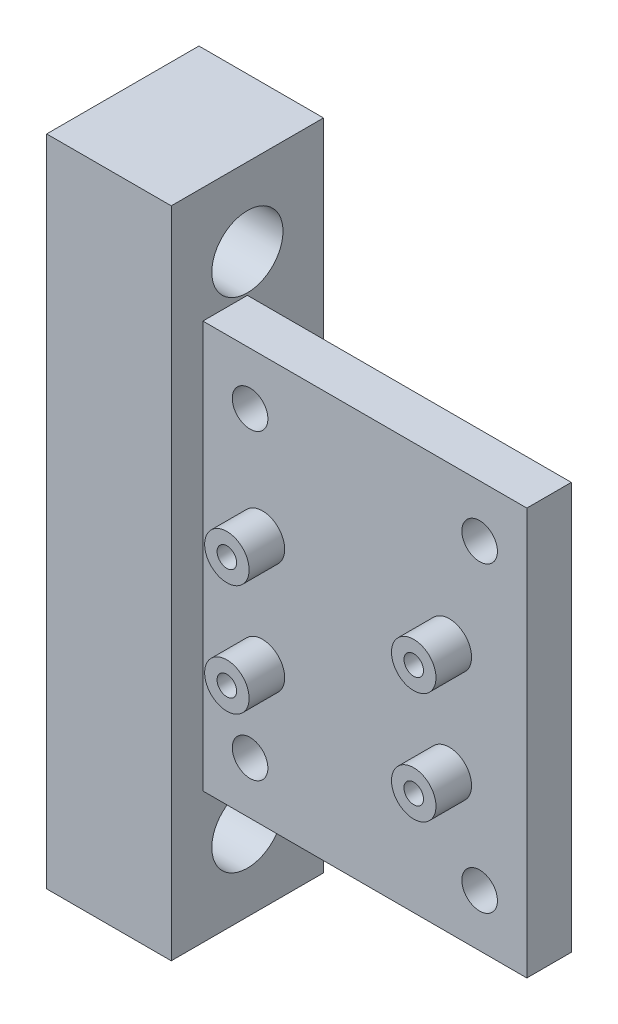
SolidWorks part; units mm, degrees
ref_plane "Ön Düzlem" through (0, 0, 0) normal (0, 0, 1) x (1, 0, 0)
ref_plane "Üst Düzlem" through (0, 0, 0) normal (0, 1, 0) x (1, 0, 0)
ref_plane "Sağ Düzlem" through (0, 0, 0) normal (1, 0, 0) x (0, 0, -1)
sketch "Çizim1" plane through (0, 0, 0) normal (0, 0, 1) x (1, 0, 0)
  line L5 (-17.8933, -21.9872) -> (18.5125, -21.9872)
  line L6 (24.7148, 0.8817) -> (-40.1845, 0.8817) construction
  line L7 (-17.8933, -21.9872) -> (-17.8933, 23.7507)
  line L8 (0.3096, 23.7507) -> (0.3096, -36.7823) construction
  line L9 (-17.8933, 23.7507) -> (18.5125, 23.7507)
  line L10 (18.5125, -21.9872) -> (18.5125, 23.7507)
  circle A0 centre (9.8019, 6.124) radius 1.1
  circle A1 centre (9.8019, -6.376) radius 1.1
  circle A2 centre (-11.1981, -6.376) radius 1.1
  circle A3 centre (-11.1981, 6.124) radius 1.1
  circle A4 centre (-11.1981, 6.124) radius 2.5
  circle A5 centre (9.8019, 6.124) radius 2.5
  circle A6 centre (9.8019, -6.376) radius 2.5
  circle A7 centre (-11.1981, -6.376) radius 2.5
  circle A12 centre (-12.5904, 17.8817) radius 2
  circle A13 centre (13.2096, 17.8817) radius 2
  circle A14 centre (13.2096, -16.1183) radius 2
  circle A15 centre (-12.5904, -16.1183) radius 2
  point P14 (0.3096, 0.8817)
extrude "Yükseklik-Ekstrüzyon3" add sketch "Çizim1" along normal blind 5 contours A7 A2 | A4 A3 | A5 A0 | A6 A1 | L5 L10 L9 L7 A15 A14 A13 A12 A7 A6 A5 A4
sketch "Çizim2" plane through (0, 0, 5) normal (0, 0, 1) x (1, 0, 0)
  circle A0 centre (-11.1981, 6.124) radius 2.5
  circle A1 centre (-11.1981, -6.376) radius 2.5
  circle A2 centre (9.8019, -6.376) radius 2.5
  circle A3 centre (9.8019, 6.124) radius 2.5
  dimension "D1" = 5
extrude "Yükseklik-Ekstrüzyon4" add sketch "Çizim2" along normal blind 4
sketch "Çizim3" plane through (0, 0, 5) normal (0, 0, -1) x (-1, 0, 0)
  circle A0 centre (11.1981, 6.124) radius 1.1 construction
  circle A1 centre (11.1981, -6.376) radius 1.1 construction
  circle A2 centre (-9.8019, -6.376) radius 1.1 construction
  circle A3 centre (-9.8019, 6.124) radius 1.1 construction
  circle A4 centre (11.1981, 6.124) radius 1.1
  circle A5 centre (11.1981, -6.376) radius 1.1
  circle A6 centre (-9.8019, -6.376) radius 1.1
  circle A7 centre (-9.8019, 6.124) radius 1.1
extrude "Kes-Ekstrüzyon1" cut sketch "Çizim3" against normal mid plane 34
sketch "Çizim4" plane through (0, 0, 0) normal (0, 0, -1) x (-1, 0, 0)
  circle A0 centre (-13.2096, 17.8817) radius 2
  circle A1 centre (12.5904, 17.8817) radius 2
  circle A2 centre (-13.2096, -16.1183) radius 2
  circle A3 centre (12.5904, -16.1183) radius 2
  circle A4 centre (-13.2096, 17.8817) radius 3.5
  circle A5 centre (12.5904, 17.8817) radius 3.5
  circle A6 centre (-13.2096, -16.1183) radius 3.5
  circle A7 centre (12.5904, -16.1183) radius 3.5
  dimension "D1" = 7
sketch "Çizim5" plane through (-17.8933, 0, 0) normal (-1, 0, 0) x (0, 0, 1)
  line L1 (-8.5554, -36.7419) -> (8.5554, -36.7419)
  line L2 (-8.5554, -36.7419) -> (-8.5554, 36.7419)
  line L3 (-8.5554, 36.7419) -> (8.5554, 36.7419)
  line L4 (8.5554, -36.7419) -> (8.5554, 36.7419)
  line L5 (-8.5554, -36.7419) -> (8.5554, 36.7419) construction
  line L6 (-8.5554, 36.7419) -> (8.5554, -36.7419) construction
  point P0 (0, 0)
extrude "Yükseklik-Ekstrüzyon6" add sketch "Çizim5" along normal blind 14
sketch "Çizim6" plane through (-17.8933, 0, 0) normal (1, 0, 0) x (0, 0, -1)
  line L0 (8.5554, 0) -> (15.4281, 0) construction
  line L1 (8.5554, 36.7419) -> (8.5554, -36.7419) construction
  circle A2 centre (0, 28) radius 4
  circle A3 centre (0, -28) radius 4
  dimension "D1" = 8
  dimension "D2" = 28
  dimension "D3" = 28
  dimension "D4" = 8
extrude "Kes-Ekstrüzyon2" cut sketch "Çizim6" against normal mid plane 62
